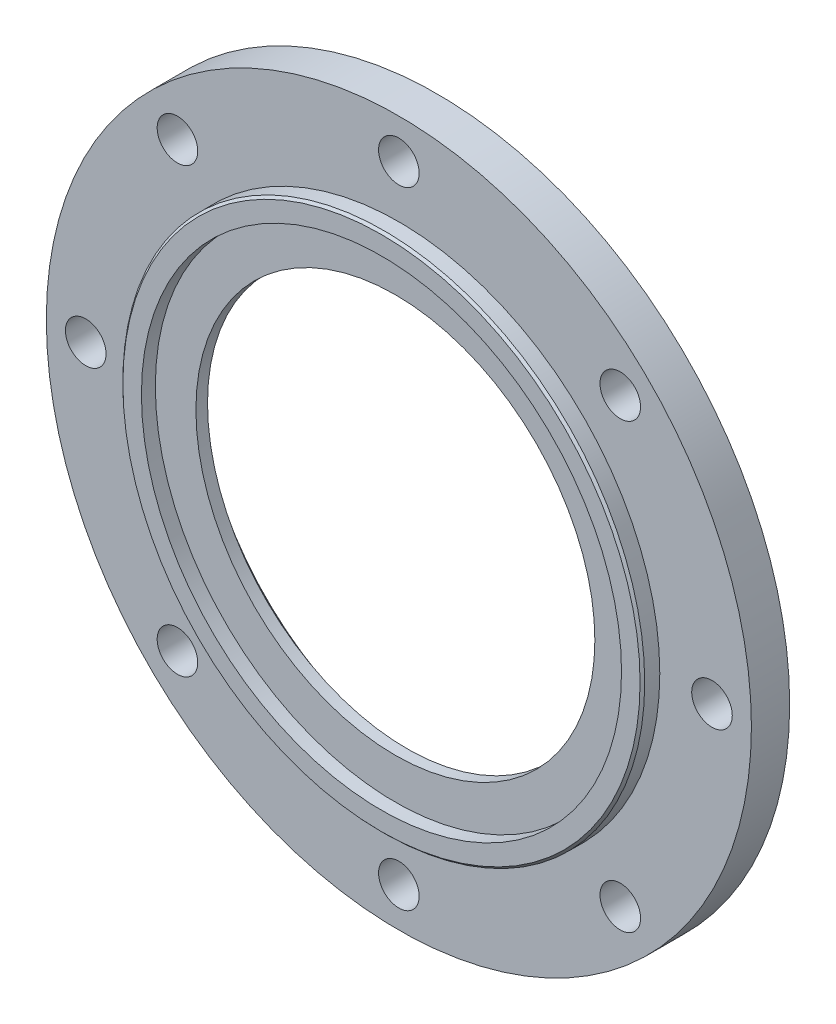
SolidWorks part; units mm, degrees
ref_plane "Front Plane" through (0, 0, 0) normal (0, 0, 1) x (1, 0, 0)
ref_plane "Top Plane" through (0, 0, 0) normal (0, 1, 0) x (1, 0, 0)
ref_plane "Right Plane" through (0, 0, 0) normal (1, 0, 0) x (0, 0, -1)
sketch "Sketch1" plane through (0, 0, 0) normal (0, 0, 1) x (1, 0, 0)
  circle A0 centre (0, 0) radius 152
  circle A3 centre (0, 0) radius 86
  dimension "D1" = 304
extrude "Boss-Extrude3" add sketch "Sketch1" along normal blind 24 contours A0 | A3
sketch "Sketch3" plane through (0, 0, 0) normal (0, 0, -1) x (-1, 0, 0)
  circle A9 centre (0, 0) radius 135
  circle A11 centre (0, 135) radius 8.75
  point P21 (0, 0)
  dimension "D1" = 270
  dimension "D2" = 17.5
sketch "Sketch5" plane through (0, 0, 24) normal (0, 0, 1) x (1, 0, 0)
  circle A0 centre (0, 0) radius 152
  circle A1 centre (0, 0) radius 112.5
  dimension "D1" = 225
extrude "Cut-Extrude6" cut sketch "Sketch5" against normal blind 7.5
sketch "Sketch6" plane through (0, 0, 24) normal (0, 0, 1) x (1, 0, 0)
  circle A0 centre (0, 0) radius 103.5
  dimension "D1" = 207
extrude "Cut-Extrude7" cut sketch "Sketch6" against normal blind 6
chamfer "Chamfer1" distance 1 angle 45 1 edges at (112.5, 0, 24)
sketch "Sketch8" plane through (0, 0, 0) normal (0, 0, -1) x (-1, 0, 0)
  circle A0 centre (0, 0) radius 117
  dimension "D1" = 234
extrude "Cut-Extrude8" cut sketch "Sketch8" against normal blind 2
sketch "Sketch16" plane through (0, 0, 2) normal (0, 0, -1) x (-1, 0, 0)
  circle A0 centre (0, 0) radius 100
  dimension "D1" = 200
extrude "Cut-Extrude9" cut sketch "Sketch16" against normal blind 11
chamfer "Chamfer3" distance 1 angle 45 1 edges at (-100, 0, 2)
sketch "Sketch19" plane through (0, 0, 2) normal (0, 0, -1) x (-1, 0, 0)
  circle A0 centre (0, 0) radius 107.5
  circle A1 centre (0, 107.5) radius 4
  dimension "D1" = 215
  dimension "D2" = 8
extrude "Cut-Extrude12" cut sketch "Sketch19" against normal blind 11 contours A1
pattern_circular "CirPattern1" count 6 over 360 about axis through (0, 0, 0) along (0, 0, 1) of "Cut-Extrude12"
extrude "Cut-Extrude13" cut sketch "Sketch3" against normal through all contours A11
pattern_circular "CirPattern2" count 8 over 360 about axis through (0, 0, 0) along (0, 0, 1) of "Cut-Extrude13"
